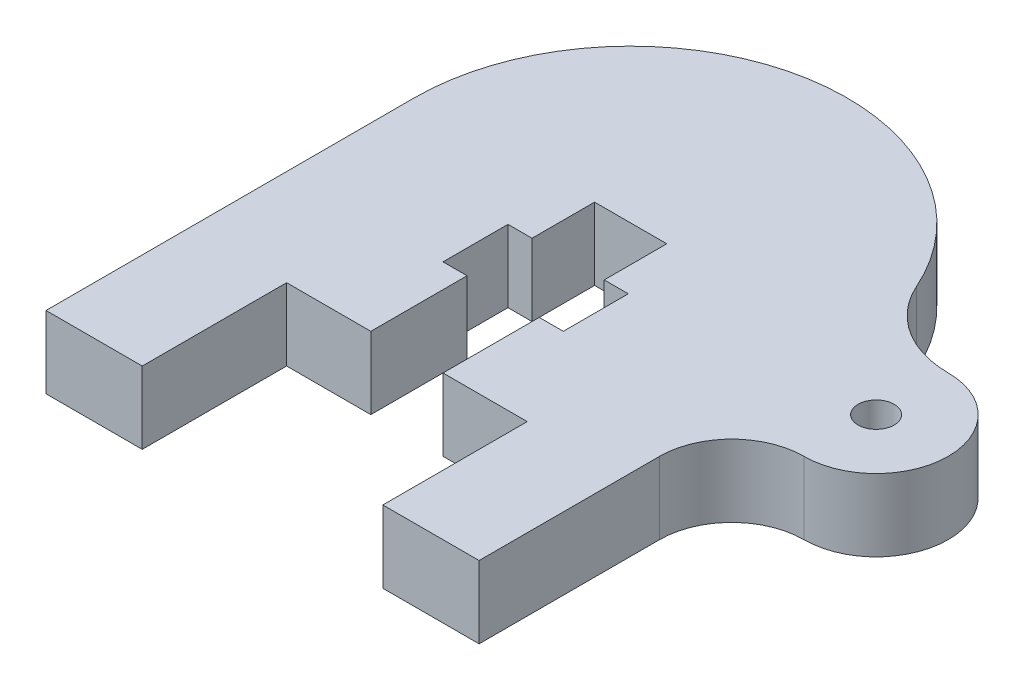
SolidWorks part; units mm, degrees
ref_plane "前视基准面" through (0, 0, 0) normal (0, 0, 1) x (1, 0, 0)
ref_plane "上视基准面" through (0, 0, 0) normal (0, 1, 0) x (1, 0, 0)
ref_plane "右视基准面" through (0, 0, 0) normal (1, 0, 0) x (0, 0, -1)
other "Configuration Table"
sketch "草图1" plane through (0, 0, 0) normal (0, 1, 0) x (1, 0, 0)
  line L0 (-41.3038, 8.1844) -> (-41.3038, -7.1156)
  line L1 (-41.3038, -7.1156) -> (-37.3038, -7.1156)
  line L2 (-37.3038, -7.1156) -> (-37.3038, -1.1156)
  line L3 (-37.3038, -1.1156) -> (-33.8038, -1.1156)
  line L4 (-33.8038, -1.1156) -> (-33.8038, 2.8844)
  line L5 (-33.8038, 2.8844) -> (-34.8038, 2.8844)
  line L6 (-34.8038, 2.8844) -> (-34.8038, 5.5844)
  line L7 (-34.8038, 5.5844) -> (-33.8038, 5.5844)
  line L8 (-33.8038, 5.5844) -> (-33.8038, 8.1844)
  line L9 (-33.8038, 8.1844) -> (-30.8038, 8.1844)
  line L10 (-32.3038, 8.1844) -> (-32.3038, 5.6844) construction
  line L11 (-30.8038, 5.5844) -> (-30.8038, 8.1844)
  line L12 (-29.8038, 5.5844) -> (-30.8038, 5.5844)
  line L13 (-30.8038, 2.8844) -> (-29.8038, 2.8844)
  line L14 (-29.8038, 2.8844) -> (-29.8038, 5.5844)
  line L15 (-30.8038, -1.1156) -> (-30.8038, 2.8844)
  line L16 (-27.3038, -1.1156) -> (-30.8038, -1.1156)
  line L17 (-27.3038, -7.1156) -> (-27.3038, -1.1156)
  line L18 (-23.3038, -7.1156) -> (-27.3038, -7.1156)
  line L19 (-23.3038, -7.1156) -> (-23.3038, 0.3844)
  line L20 (-23.3038, 0.3844) -> (-20.3038, 0.3844) construction
  line L21 (-20.3038, 0.3844) -> (-20.3038, 6.3844) construction
  line L22 (-20.3038, 6.3844) -> (-20.3038, 12.3844) construction
  arc A0 (-23.3038, 0.3844) -> (-20.3038, 3.3844) centre (-20.3038, 0.3844) cw
  arc A1 (-20.3038, 3.3844) -> (-20.3038, 9.3844) centre (-20.3038, 6.3844) ccw
  arc A2 (-41.3038, 8.1844) -> (-24.0788, 11.8382) centre (-32.3038, 8.1844) cw
  arc A4 (-20.3038, 9.3844) -> (-24.0788, 11.8382) centre (-20.3038, 13.5152) cw
  circle A5 centre (-20.3038, 6.3844) radius 0.75
  point P31 (-20.3038, 13.5152)
extrude "凸台-拉伸1" add sketch "草图1" along normal blind 3
